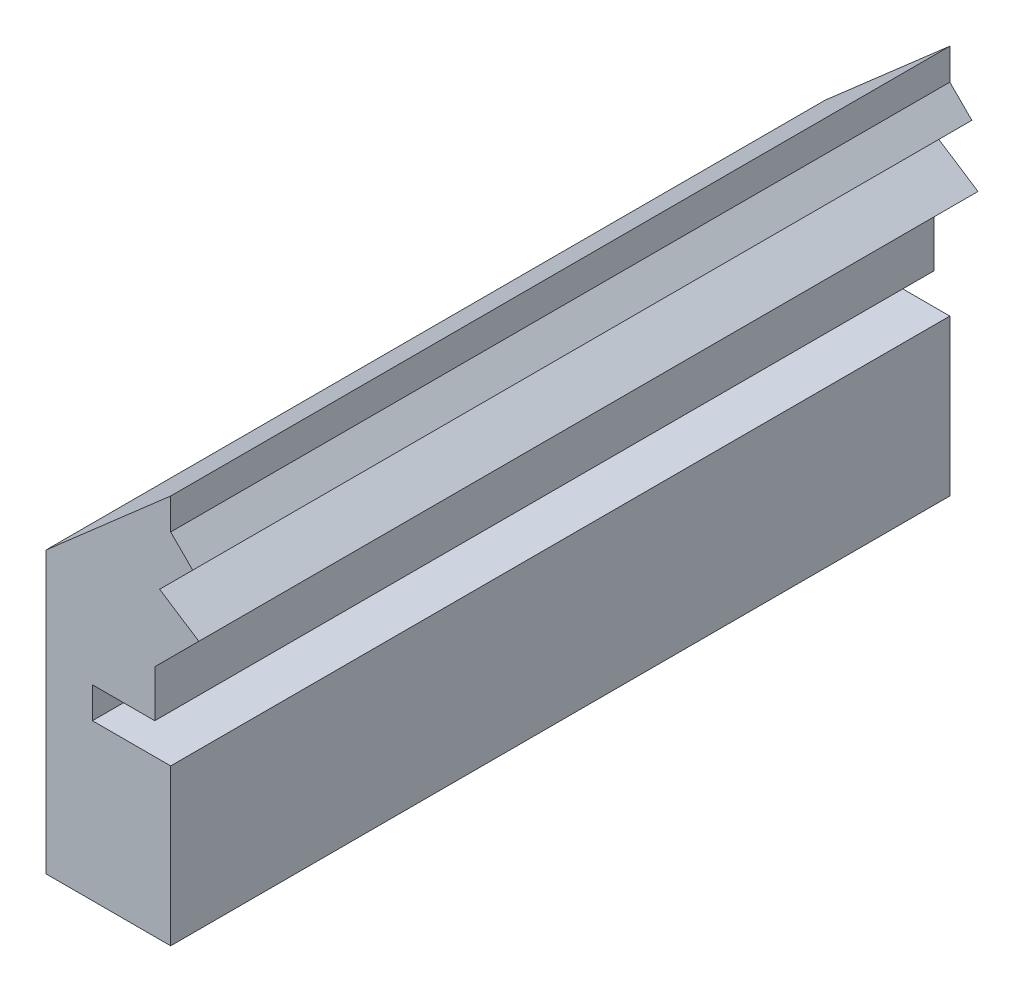
SolidWorks part; units mm, degrees
ref_plane "Front Plane" through (0, 0, 0) normal (0, 0, 1) x (1, 0, 0)
ref_plane "Top Plane" through (0, 0, 0) normal (0, 1, 0) x (1, 0, 0)
ref_plane "Right Plane" through (0, 0, 0) normal (1, 0, 0) x (0, 0, -1)
sketch "Sketch1" plane through (0, 0, 0) normal (0, 0, 1) x (1, 0, 0)
  line L0 (0, 0) -> (0, -10)
  line L1 (0, -10) -> (7.0711, -17.0711)
  line L2 (7.0711, -17.0711) -> (-3.5355, -27.6777)
  line L3 (-3.5355, -27.6777) -> (9.0376, -35.8579)
  line L4 (9.0376, -35.8579) -> (-5.1045, -50)
  line L5 (-5.1045, -50) -> (-5.1045, -65)
  line L6 (-5.1045, -65) -> (-25.1045, -65)
  line L7 (-25.1045, -65) -> (-25.1045, -75)
  line L8 (-25.1045, -75) -> (0, -75)
  line L9 (0, -75) -> (0, -125)
  line L10 (0, -125) -> (-40, -125)
  line L11 (-40, -125) -> (-40, -35)
  line L12 (-40, -35) -> (0, 0)
  line L13 (-639.6625, -66.2865) -> (-611.4192, -66.2865) construction
  line L14 (-620.6566, -59.6489) -> (-639.6625, -59.6489) construction
  line L15 (-687.1874, -47.636) -> (-611.4294, 0) construction
  line L16 (-620.6566, -47.636) -> (-620.6566, -59.6489) construction
  line L17 (-611.4192, -66.2865) -> (-611.4192, -92.0402) construction
  line L18 (-687.1874, -92.0402) -> (-687.1874, -47.636) construction
  line L19 (-611.4294, -10) -> (-602.1817, -19.2476) construction
  line L20 (-639.6625, -59.6489) -> (-639.6625, -66.2865) construction
  line L21 (-611.4192, -92.0402) -> (-687.1874, -92.0402) construction
  line L22 (-602.1817, -19.2476) -> (-620.6566, -28.4749) construction
  line L23 (-602.1817, -38.4087) -> (-620.6566, -47.636) construction
  line L24 (-620.6566, -28.4749) -> (-602.1817, -38.4087) construction
  line L25 (-611.4294, 0) -> (-611.4294, -10) construction
  dimension "D1" = 10
  dimension "D2" = 10
  dimension "D3" = 15
  dimension "D4" = 15
  dimension "D5" = 20
  dimension "D6" = 15
  dimension "D7" = 20
  dimension "D8" = 10
  dimension "D9" = 50
  dimension "D10" = 90
  dimension "D11" = 40
  dimension "D12" = 35
  dimension "D13" = 135
  dimension "D14" = 90
extrude "Boss-Extrude1" add sketch "Sketch1" along normal blind 250
